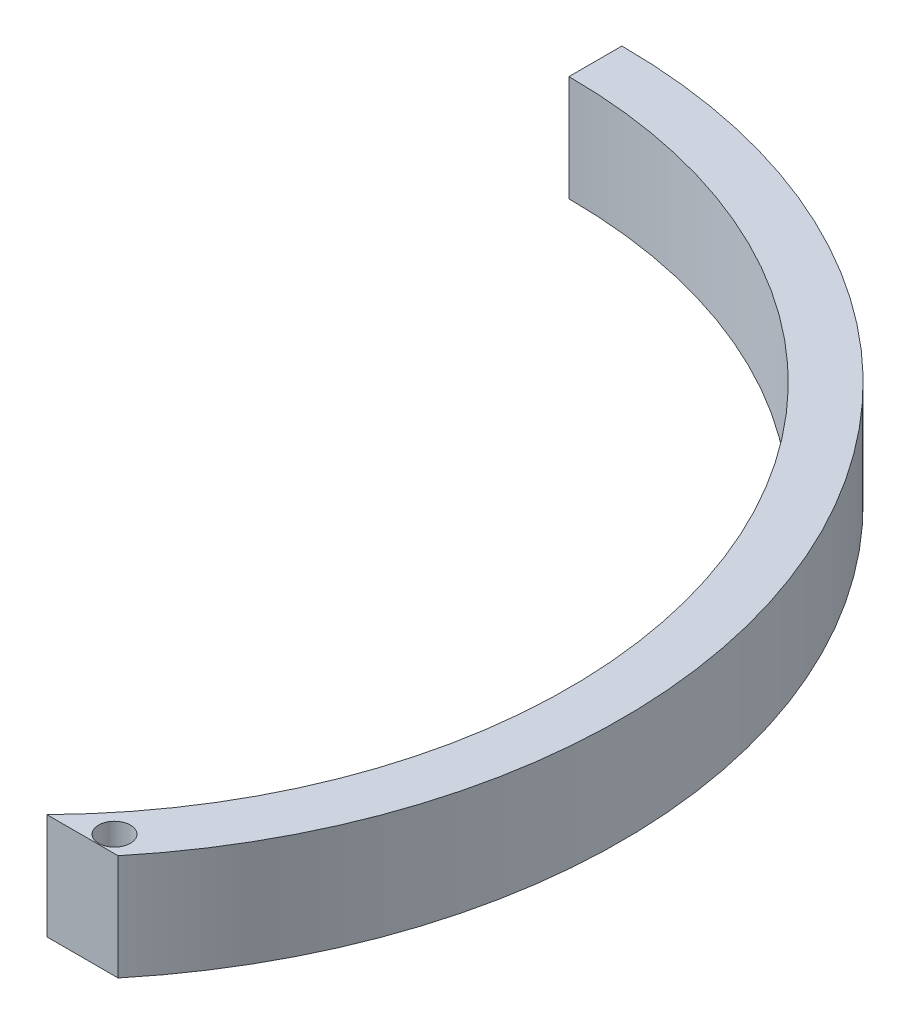
SolidWorks part; units mm, degrees
material "1060 Alloy"
ref_plane "Front Plane" through (0, 0, 0) normal (0, 0, 1) x (1, 0, 0)
ref_plane "Top Plane" through (0, 0, 0) normal (0, 1, 0) x (1, 0, 0)
ref_plane "Right Plane" through (0, 0, 0) normal (1, 0, 0) x (0, 0, -1)
sketch "Sketch1" plane through (0, 0, 0) normal (0, 1, 0) x (1, 0, 0)
  line L0 (0, 55) -> (0, -55) construction
  line L1 (-50, -35) -> (75, -35) construction
  line L2 (0, 50) -> (0, 55)
  line L5 (35.7071, -35) -> (42.4264, -35)
  line L6 (42.4264, -35) -> (38.5695, -31.8182) construction
  arc A3 (35.7071, -35) -> (0, 50) centre (0, 0) ccw
  arc A4 (42.4264, -35) -> (0, 55) centre (0, 0) ccw
  circle A5 centre (40.4979, -33.4091) radius 1.5
  dimension "D1" = 100
  dimension "D2" = 110
  dimension "D3" = 90
  dimension "D4" = 3
extrude "Boss-Extrude2" add sketch "Sketch1" along normal blind 10
